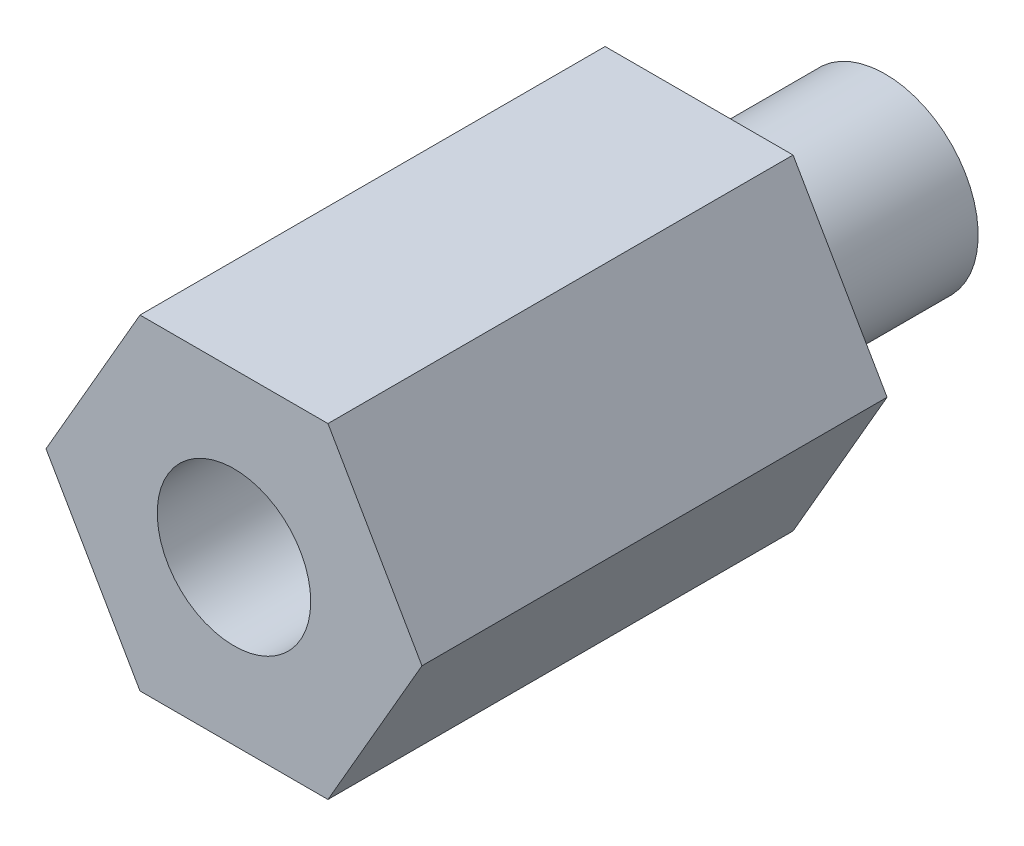
SolidWorks part; units mm, degrees
material "黃銅"
ref_plane "前基準面" through (0, 0, 0) normal (0, 0, 1) x (1, 0, 0)
ref_plane "上基準面" through (0, 0, 0) normal (0, 1, 0) x (1, 0, 0)
ref_plane "右基準面" through (0, 0, 0) normal (1, 0, 0) x (0, 0, -1)
sketch "草圖1" plane through (0, 0, 0) normal (0, 0, 1) x (1, 0, 0)
  line L1 (-2.0207, 3.5) -> (-4.0415, 0)
  line L2 (-4.0415, 0) -> (-2.0207, -3.5)
  line L3 (-2.0207, -3.5) -> (2.0207, -3.5)
  line L4 (2.0207, -3.5) -> (4.0415, 0)
  line L5 (4.0415, 0) -> (2.0207, 3.5)
  line L6 (2.0207, 3.5) -> (-2.0207, 3.5)
  circle A0 centre (0, 0) radius 3.5 construction
  dimension "D1" = 7
extrude "填料-伸長1" add sketch "草圖1" along normal blind 10
sketch "草圖4" plane through (0, 0, 0) normal (0, 0, -1) x (-1, 0, 0)
  circle A0 centre (0, 0) radius 2
  dimension "D1" = 4
extrude "填料-伸長2" add sketch "草圖4" along normal blind 4
hole_wizard "M4x0.7 螺紋孔1" positions "草圖2" profile "草圖3" tap size "M4x0.7" standard "Ansi Metric"
sketch "草圖2" plane through (0, 0, 10) normal (0, 0, 1) x (1, 0, 0)
  point P0 (0, 0)
sketch "草圖3" plane through (0, 0, 10) normal (1, 0, 0) x (0, -1, 0)
  line L0 (0, 0) -> (0, 8.9914)
  line L1 (0, 8.9914) -> (1.65, 8)
  line L2 (1.65, 8) -> (1.65, 0)
  line L5 (1.65, 0) -> (0, 0)
  line L10 (0, 8.9914) -> (-1.65, 8) construction
  line L11 (0, -6.35) -> (0, 107.95) construction
  dimension "螺孔鑽直徑" = 3.3
  dimension "螺孔鑽深度" = 8
  dimension "導頭角度" = 118
